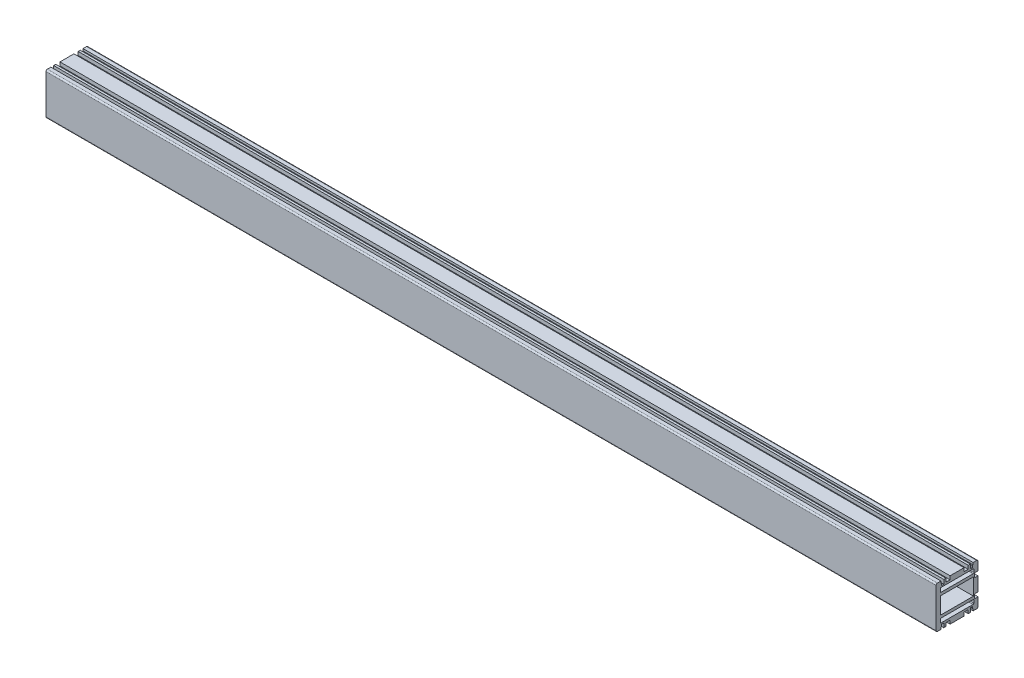
SolidWorks part; units mm, degrees
ref_plane "前视基准面" through (0, 0, 0) normal (0, 0, 1) x (1, 0, 0)
ref_plane "上视基准面" through (0, 0, 0) normal (0, 1, 0) x (1, 0, 0)
ref_plane "右视基准面" through (0, 0, 0) normal (1, 0, 0) x (0, 0, -1)
sketch "草图1" plane through (0, 0, 0) normal (1, 0, 0) x (0, 0, -1)
  line L0 (-15, 15) -> (15, -15) construction
  line L1 (-14, 15) -> (-11.5, 15)
  line L2 (-15, 14) -> (-15, -14)
  line L3 (-14, -15) -> (-11.5, -15)
  line L4 (15, 14) -> (15, 8)
  line L5 (15, 15) -> (-15, -15) construction
  line L6 (-11.5, 15) -> (-11.5, 13.5)
  line L7 (-11.5, 13.5) -> (-11.4, 13.5)
  line L8 (-11, 13.1) -> (-11, 12)
  line L9 (-11, 12) -> (-9.5, 12)
  line L10 (-9.5, 12) -> (-9.5, 15)
  line L11 (-9.5, 15) -> (-8, 15)
  line L12 (-8, 15) -> (-8, 12.5)
  line L13 (-8, 12.5) -> (-5, 12.5)
  line L14 (-5, 12.5) -> (-5, 15)
  line L15 (-5, 15) -> (5, 15)
  line L16 (0, 21.5201) -> (0, -18.309) construction
  line L17 (0, 55) -> (0, -55) construction
  line L18 (5, 12.5) -> (5, 15)
  line L19 (8, 12.5) -> (5, 12.5)
  line L20 (8, 15) -> (8, 12.5)
  line L21 (9.5, 15) -> (8, 15)
  line L22 (9.5, 12) -> (9.5, 15)
  line L23 (11, 12) -> (9.5, 12)
  line L24 (11, 13.1) -> (11, 12)
  line L25 (11.5, 13.5) -> (11.4, 13.5)
  line L26 (11.5, 15) -> (11.5, 13.5)
  line L27 (8, 15) -> (9.5, 15)
  line L28 (11.5, 15) -> (14, 15)
  line L29 (-19.8303, 0) -> (22.13, 0) construction
  line L30 (55, 0) -> (-55, 0) construction
  line L31 (8, -15) -> (9.5, -15)
  line L32 (11.5, -15) -> (11.5, -13.5)
  line L33 (11.5, -13.5) -> (11.4, -13.5)
  line L34 (11, -13.1) -> (11, -12)
  line L35 (11, -12) -> (9.5, -12)
  line L36 (9.5, -12) -> (9.5, -15)
  line L37 (9.5, -15) -> (8, -15)
  line L38 (8, -15) -> (8, -12.5)
  line L39 (8, -12.5) -> (5, -12.5)
  line L40 (5, -12.5) -> (5, -15)
  line L41 (-5, -15) -> (5, -15)
  line L42 (-5, -12.5) -> (-5, -15)
  line L43 (-8, -12.5) -> (-5, -12.5)
  line L44 (-8, -15) -> (-8, -12.5)
  line L45 (-9.5, -15) -> (-8, -15)
  line L46 (-9.5, -12) -> (-9.5, -15)
  line L47 (-11, -12) -> (-9.5, -12)
  line L48 (-11, -13.1) -> (-11, -12)
  line L49 (-11.5, -13.5) -> (-11.4, -13.5)
  line L50 (-11.5, -15) -> (-11.5, -13.5)
  line L51 (-9.5, -15) -> (-8, -15)
  line L52 (-5, -15) -> (5, -15)
  line L53 (8, -15) -> (9.5, -15)
  line L54 (11.5, -15) -> (14, -15)
  line L55 (15, 8) -> (12.5, 8)
  line L56 (12.5, 8) -> (12.5, 5)
  line L57 (12.5, 5) -> (15, 5)
  line L58 (12.5, -5) -> (15, -5)
  line L59 (12.5, -8) -> (12.5, -5)
  line L60 (15, -8) -> (12.5, -8)
  line L61 (15, 5) -> (15, -5)
  line L62 (15, -8) -> (15, -14)
  line L63 (12, -10.5) -> (12, -8.5)
  line L64 (-11.5, 11) -> (11.5, 11)
  line L65 (-12, 10.5) -> (-12, 8.5)
  line L66 (-11.5, 8) -> (11.5, 8)
  line L67 (12, 10.5) -> (12, 8.5)
  line L68 (-11.5, -8) -> (11.5, -8)
  line L69 (-12, -10.5) -> (-12, -8.5)
  line L70 (-11.5, -11) -> (11.5, -11)
  line L72 (-11.75, 6) -> (11.75, 6)
  line L73 (-11.75, 6) -> (-11.75, -6)
  line L74 (-11.75, -6) -> (11.75, -6)
  line L75 (11.75, 6) -> (11.75, -6)
  arc A0 (12, 8.5) -> (11.5, 8) centre (11.5, 8.5) cw
  arc A1 (11.5, 11) -> (12, 10.5) centre (11.5, 10.5) cw
  arc A2 (-11.5, 11) -> (-12, 10.5) centre (-11.5, 10.5) ccw
  arc A3 (-11.5, 8) -> (-12, 8.5) centre (-11.5, 8.5) cw
  arc A4 (-11, -13.1) -> (-11.4, -13.5) centre (-11.4, -13.1) cw
  arc A5 (11.4, -13.5) -> (11, -13.1) centre (11.4, -13.1) cw
  arc A6 (11.4, 13.5) -> (11, 13.1) centre (11.4, 13.1) ccw
  arc A7 (-11, 13.1) -> (-11.4, 13.5) centre (-11.4, 13.1) ccw
  arc A8 (-11.5, -8) -> (-12, -8.5) centre (-11.5, -8.5) ccw
  arc A9 (-11.5, -11) -> (-12, -10.5) centre (-11.5, -10.5) cw
  arc A10 (11.5, -11) -> (12, -10.5) centre (11.5, -10.5) ccw
  arc A11 (12, -8.5) -> (11.5, -8) centre (11.5, -8.5) ccw
  arc A12 (14, 15) -> (15, 14) centre (14, 14) cw
  arc A13 (14, -15) -> (15, -14) centre (14, -14) ccw
  arc A14 (-15, -14) -> (-14, -15) centre (-14, -14) ccw
  arc A15 (-15, 14) -> (-14, 15) centre (-14, 14) cw
  point P69 (12, 11)
  point P72 (-12, 11)
  point P77 (-11, -13.5)
  point P80 (11, -13.5)
  point P83 (11, 13.5)
  point P86 (-11, 13.5)
  point P99 (-12, -11)
  point P100 (12, -11)
  dimension "D17" = 0.5
  dimension "D18" = 0.4
  dimension "D21" = 1
  dimension "D1" = 3.5
  dimension "D2" = 1.5
  dimension "D3" = 0.5
  dimension "D4" = 1.5
  dimension "D5" = 3
  dimension "D6" = 30
  dimension "D7" = 30
  dimension "D8" = 1.5
  dimension "D9" = 2.5
  dimension "D10" = 3
  dimension "D11" = 2.5
  dimension "D12" = 7
  dimension "D13" = 3
  dimension "D14" = 4
  dimension "D15" = 3
  dimension "D16" = 24
  dimension "D19" = 23.5
  dimension "D20" = 12
extrude "凸台-拉伸1" add sketch "草图1" along normal mid plane 637 contours A15 L2 A14 L3 L50 L49 A4 L48 L47 L46 L45 L44 L43 L42 L41 L40 L39 L38 L31 L36 L35 L34 A5 L33 L32 L54 A13 L62 L60 L59 L58 L61 L57 L56 L55 L4 A12 L28 L26 L25 A6 L24 L23 L22 L21 L20 L19 L18 L15 L14 L13
hole_wizard "M6 螺纹孔1" positions "草图3" profile "草图2" tap size "M6" standard "GB"
sketch "草图3" plane through (0, 0, -15) normal (0, 0, -1) x (-1, 0, 0)
  line L0 (318.5, 5) -> (318.5, -5) construction
  point P0 (298.5, -0.1437)
  point P1 (283.5, 0)
  dimension "D1" = 20
sketch "草图2" plane through (-298.5, -0.1437, -15) normal (1, 0, 0) x (0, 1, 0)
  line L0 (0, 0) -> (0, 16.5022)
  line L1 (0, 16.5022) -> (2.5, 15)
  line L2 (2.5, 15) -> (2.5, 0)
  line L5 (2.5, 0) -> (0, 0)
  line L10 (0, 16.5022) -> (-2.5, 15) construction
  line L11 (0, -6.35) -> (0, 107.95) construction
  dimension "螺纹孔钻头直径" = 5
  dimension "螺纹孔钻头深度" = 15
  dimension "导头角度" = 118
cosmetic thread "孔螺蚊线1" parameters "D1"=3.25, "D2"=6
cosmetic thread "孔螺蚊线2" parameters "D1"=3.25, "D2"=6
hole_wizard "M6 螺纹孔2" positions "草图5" profile "草图4" tap size "M6" standard "GB"
sketch "草图5" plane through (0, -15, 0) normal (0, -1, 0) x (1, 0, 0)
  line L0 (-318.5, 5) -> (-318.5, -5) construction
  line L1 (318.5, -15) -> (-318.5, -15) construction
  point P0 (-298.5, 0)
  point P1 (-283.5, 0)
  point P4 (283.5, 0)
  point P7 (298.5, 0)
  dimension "D1" = 20
  dimension "D2" = 15
sketch "草图4" plane through (-298.5, -15, 0) normal (1, 0, 0) x (0, 0, -1)
  line L0 (0, 0) -> (0, 16.5022)
  line L1 (0, 16.5022) -> (2.5, 15)
  line L2 (2.5, 15) -> (2.5, 0)
  line L5 (2.5, 0) -> (0, 0)
  line L10 (0, 16.5022) -> (-2.5, 15) construction
  line L11 (0, -6.35) -> (0, 107.95) construction
  dimension "螺纹孔钻头直径" = 5
  dimension "螺纹孔钻头深度" = 15
  dimension "导头角度" = 118
cosmetic thread "孔螺蚊线3" parameters "D1"=9, "D2"=6
cosmetic thread "孔螺蚊线4" parameters "D1"=9, "D2"=6
cosmetic thread "孔螺蚊线5" parameters "D1"=9, "D2"=6
cosmetic thread "孔螺蚊线6" parameters "D1"=9, "D2"=6
hole_wizard "M4 螺纹孔1" positions "草图7" profile "草图6" tap size "M4" standard "GB"
sketch "草图7" plane through (0, 0, -15) normal (0, 0, -1) x (-1, 0, 0)
  line L0 (-318.5, 5) -> (-318.5, -5) construction
  line L1 (-318.5, 15) -> (318.5, 15) construction
  line L2 (-318.5, 15) -> (318.5, 15) construction
  line L3 (-318.5, 15) -> (318.5, 15) construction
  point P1 (-303.5, 0)
  point P3 (-118.5, 0)
  point P5 (66.5, 0)
  point P7 (251.5, 0)
  dimension "D1" = 15
  dimension "D2" = 15
  dimension "D3" = 185
  dimension "D4" = 15
  dimension "D5" = 185
  dimension "D6" = 15
  dimension "D7" = 185
  dimension "D8" = 15
sketch "草图6" plane through (303.5, 0, -15) normal (1, 0, 0) x (0, 1, 0)
  line L0 (0, 0) -> (0, 11.0914)
  line L1 (0, 11.0914) -> (1.65, 10.1)
  line L2 (1.65, 10.1) -> (1.65, 0)
  line L5 (1.65, 0) -> (0, 0)
  line L10 (0, 11.0914) -> (-1.65, 10.1) construction
  line L11 (0, -6.35) -> (0, 107.95) construction
  dimension "螺纹孔钻头直径" = 3.3
  dimension "螺纹孔钻头深度" = 10.1
  dimension "导头角度" = 118
cosmetic thread "孔螺蚊线7" parameters "D1"=3.25, "D2"=4
cosmetic thread "孔螺蚊线8" parameters "D1"=3.25, "D2"=4
cosmetic thread "孔螺蚊线9" parameters "D1"=3.25, "D2"=4
cosmetic thread "孔螺蚊线10" parameters "D1"=3.25, "D2"=4
